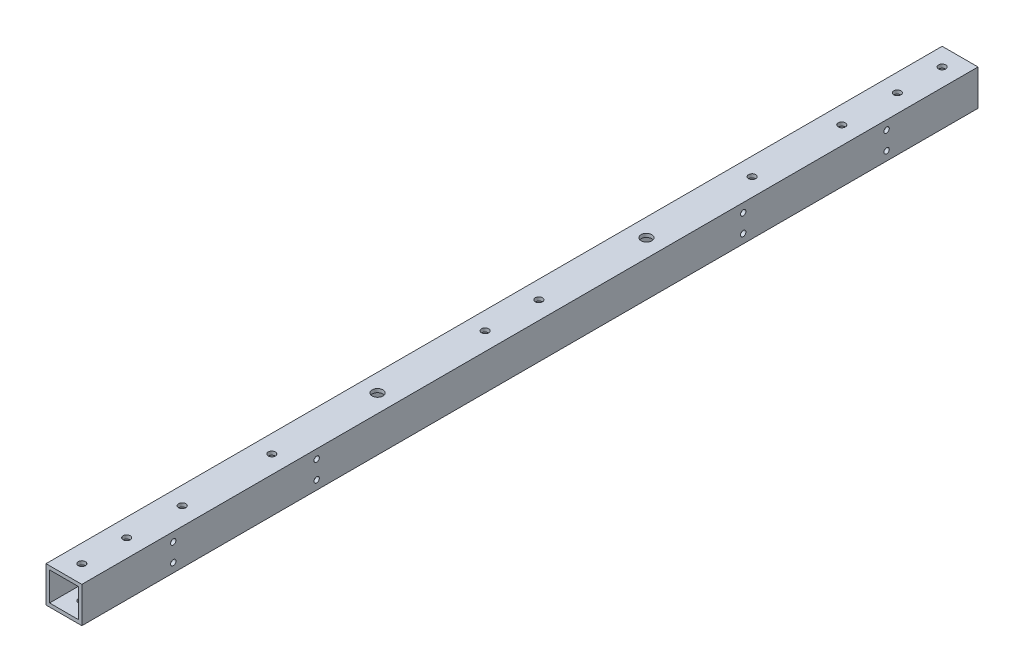
SolidWorks part; units mm, degrees
ref_plane "前视基准面" through (0, 0, 0) normal (0, 0, 1) x (1, 0, 0)
ref_plane "上视基准面" through (0, 0, 0) normal (0, 1, 0) x (1, 0, 0)
ref_plane "右视基准面" through (0, 0, 0) normal (1, 0, 0) x (0, 0, -1)
other "Configuration Table"
sketch "草图1" plane through (0, 0, 0) normal (0, 0, 1) x (1, 0, 0)
  line L0 (0, 2) -> (2, 2) construction
  line L1 (0, 0) -> (20, 0)
  line L2 (0, 0) -> (0, 20)
  line L3 (0, 20) -> (20, 20)
  line L4 (20, 0) -> (20, 20)
  line L5 (2, 18) -> (18, 18)
  line L6 (2, 18) -> (2, 2)
  line L7 (2, 2) -> (18, 2)
  line L8 (18, 18) -> (18, 2)
  line L9 (2, 2) -> (2, 0) construction
  line L10 (18, 20) -> (18, 18) construction
  line L11 (18, 18) -> (20, 18) construction
  dimension "D1" = 20
  dimension "D2" = 20
  dimension "D3" = 2
extrude "凸台-拉伸1" add sketch "草图1" along normal blind 500
sketch "草图2" plane through (0, 0, 0) normal (0, 1, 0) x (1, 0, 0)
  line L0 (0, -250) -> (20, -250) construction
  line L1 (0, -500) -> (0, 0) construction
  line L2 (20, -500) -> (20, 0) construction
  line L3 (10, -250) -> (10, 0) construction
  line L4 (20, 0) -> (0, 0) construction
  line L5 (12, -66) -> (12, -116) construction
  line L6 (12, -91) -> (20, -91) construction
  circle A0 centre (10, -175) radius 3
  circle A1 centre (10, -325) radius 3
  circle A2 centre (10, -10) radius 2
  circle A3 centre (10, -66) radius 2
  circle A4 centre (10, -116) radius 2
  circle A5 centre (10, -35) radius 2
  circle A6 centre (10, -384) radius 2
  circle A7 centre (10, -434) radius 2
  circle A8 centre (10, -465) radius 2
  circle A9 centre (10, -490) radius 2
  dimension "D1" = 6
  dimension "D2" = 150
  dimension "D3" = 50
  dimension "D4" = 4
  dimension "D5" = 4
  dimension "D7" = 25
  dimension "D8" = 10
  dimension "D9" = 159
  dimension "D6" = 2
extrude "切除-拉伸1" cut sketch "草图2" along normal through all
sketch "草图3" plane through (0, 0, 0) normal (1, 0, 0) x (0, 0, -1)
  line L0 (-250, 20) -> (-250, 0) construction
  line L1 (-500, 20) -> (0, 20) construction
  line L2 (-500, 0) -> (0, 0) construction
  line L3 (-250, 10) -> (-500, 10) construction
  line L4 (-500, 0) -> (-500, 20) construction
  line L5 (-449, 20) -> (-449, 10) construction
  line L6 (-409, 10) -> (-409, 20) construction
  line L7 (-500, 20) -> (0, 20) construction
  circle A0 centre (-449, 15) radius 1.5
  circle A1 centre (-449, 5) radius 1.5
  circle A2 centre (-369, 5) radius 1.5
  circle A3 centre (-369, 15) radius 1.5
  circle A4 centre (-131, 15) radius 1.5
  circle A5 centre (-131, 5) radius 1.5
  circle A6 centre (-51, 5) radius 1.5
  circle A7 centre (-51, 15) radius 1.5
  dimension "D1" = 80
  dimension "D3" = 3
  dimension "D2" = 159
extrude "切除-拉伸2" cut sketch "草图3" along normal through all
sketch "草图4" plane through (0, 20, 0) normal (0, 1, 0) x (1, 0, 0)
  line L0 (10, -265) -> (10, -235) construction
  line L1 (10, -250) -> (20, -250) construction
  line L2 (20, -500) -> (20, 0) construction
  circle A0 centre (10, -265) radius 2
  circle A1 centre (10, -235) radius 2
  point P8 (10.9688, -250)
  dimension "D2" = 4
  dimension "D1" = 30
  dimension "D3" = 10
extrude "切除-拉伸3" cut sketch "草图4" against normal through all
